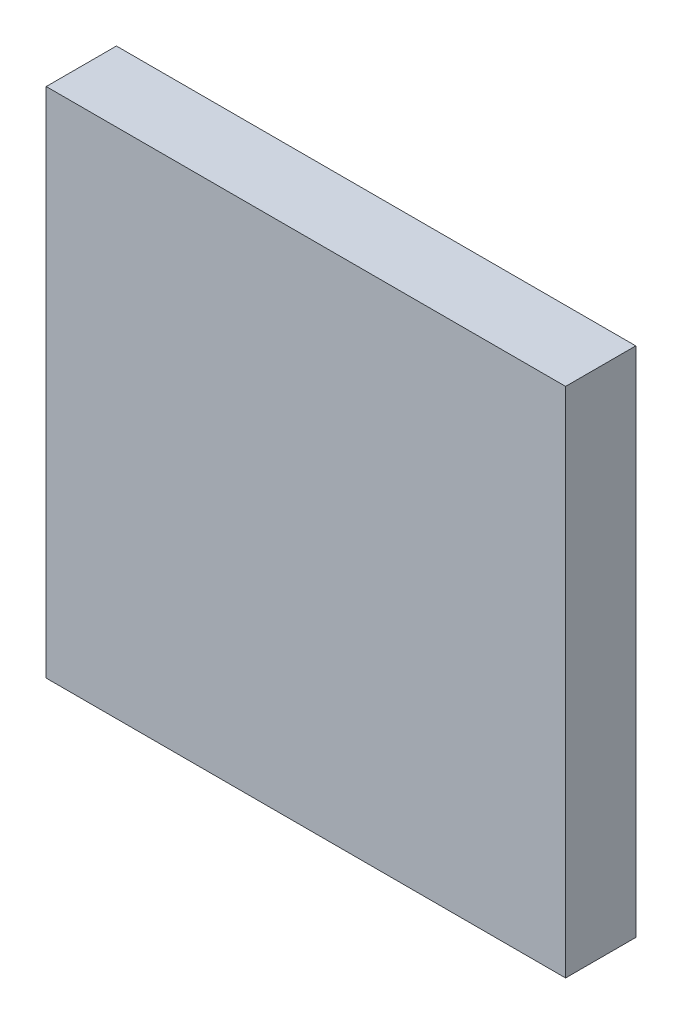
SolidWorks part; units mm, degrees
ref_plane "前视基准面" through (0, 0, 0) normal (0, 0, 1) x (1, 0, 0)
ref_plane "上视基准面" through (0, 0, 0) normal (0, 1, 0) x (1, 0, 0)
ref_plane "右视基准面" through (0, 0, 0) normal (1, 0, 0) x (0, 0, -1)
sketch "草图1" plane through (0, 0, 0) normal (0, 0, 1) x (1, 0, 0)
  line L0 (-3.7, 3.65) -> (-3.7, -3.65)
  line L1 (-3.7, -3.65) -> (3.7, -3.65)
  line L2 (3.7, -3.65) -> (3.7, 3.65)
  line L3 (3.7, 3.65) -> (-3.7, 3.65)
extrude "Component_Outline" add sketch "草图1" along normal blind 1 separate body
sketch3d "3D草图1"
  line L0 (0, 0, 0) -> (1, 0, 0)
  line L1 (0, 0, 0) -> (0, 1, 0)
  line L2 (0, 0, 0) -> (0, 0, 1)
  point P0 (0, 0, 0)
